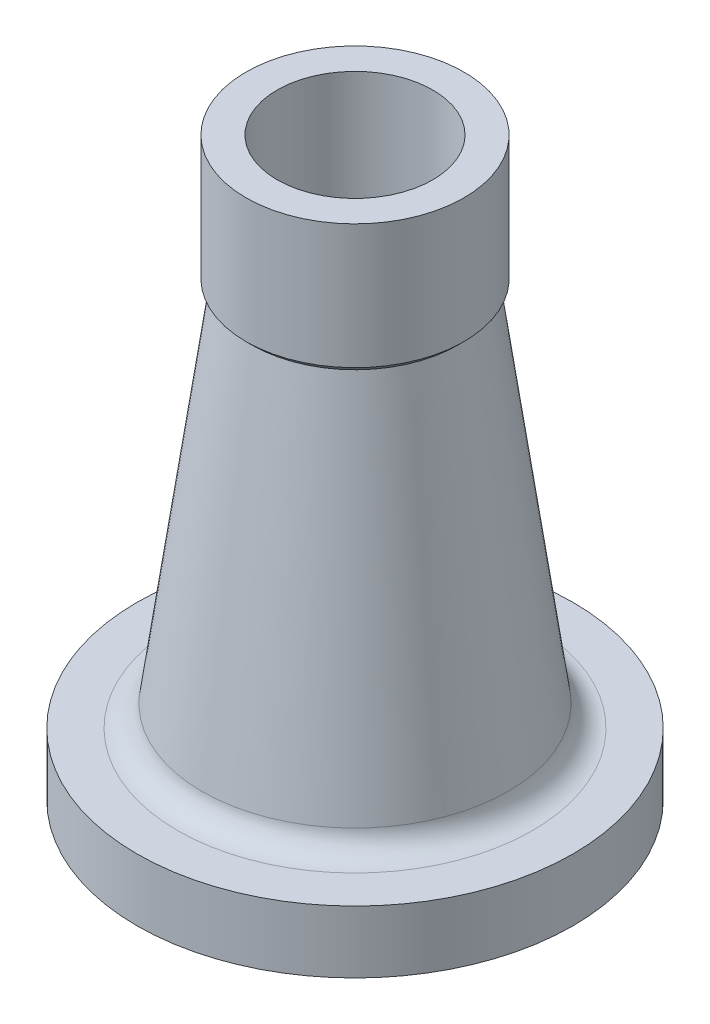
SolidWorks part; units mm, degrees
ref_plane "Front Plane" through (0, 0, 0) normal (0, 0, 1) x (1, 0, 0)
ref_plane "Top Plane" through (0, 0, 0) normal (0, 1, 0) x (1, 0, 0)
ref_plane "Right Plane" through (0, 0, 0) normal (1, 0, 0) x (0, 0, -1)
sketch "Sketch1" plane through (0, 0, 0) normal (0, 0, 1) x (1, 0, 0)
  line L0 (0, 99.49) -> (0, -108.8027) construction
  line L1 (0, 0) -> (70, 0) construction
  line L2 (70, 0) -> (70, 20)
  line L3 (70, 20) -> (57, 20)
  line L4 (0, 185) -> (35, 185) construction
  line L5 (35, 185) -> (35, 145)
  line L6 (35, 145) -> (33, 143)
  line L7 (25, 127.867) -> (42.2899, 3)
  line L8 (33, 143) -> (49.0756, 26.9027)
  line L9 (25, 185) -> (25, 127.867)
  line L10 (50, 0) -> (50, 1)
  line L11 (50, 0) -> (70, 0)
  line L12 (48, 3) -> (42.2899, 3)
  line L13 (25, 185) -> (35, 185)
  arc A0 (49.0756, 26.9027) -> (57, 20) centre (57, 28) ccw
  arc A1 (50, 1) -> (48, 3) centre (48, 1) ccw
  point P18 (50, 0.5)
  point P24 (50, 3)
  dimension "D4" = 16
  dimension "D14" = 2
  dimension "D1" = 70
  dimension "D2" = 20
  dimension "D3" = 57
  dimension "D5" = 35
  dimension "D6" = 40
  dimension "D7" = 185
  dimension "D8" = 33
  dimension "D9" = 135
  dimension "D10" = 10
  dimension "D11" = 10
  dimension "D12" = 3
  dimension "D13" = 50
revolve "Revolve1" add sketch "Sketch1" angle 360 about L0
